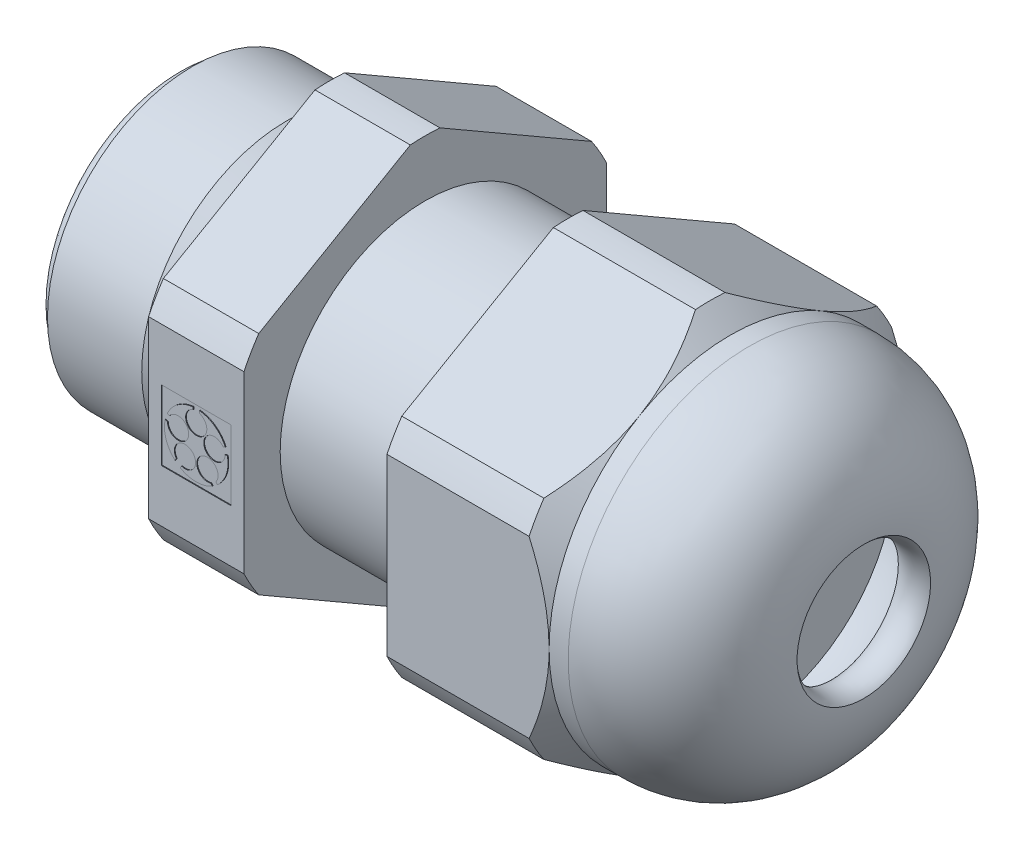
SolidWorks part; units mm, degrees
ref_plane "Face" through (0, 0, 0) normal (0, 0, 1) x (1, 0, 0)
ref_plane "Dessus" through (0, 0, 0) normal (0, 1, 0) x (1, 0, 0)
ref_plane "Droite" through (0, 0, 0) normal (1, 0, 0) x (0, 0, -1)
ref_plane "Plan1" through (0, 0, 0) normal (0, 0, 1) x (1, 0, 0)
sketch "Esquisse1" plane through (0, 0, 0) normal (0, 0, 1) x (1, 0, 0)
  line L0 (0.585, 1.75) -> (30, 1.75)
  line L1 (30, 1.75) -> (30, 7.6)
  line L2 (30, 9.5) -> (29, 9.5)
  line L3 (29, 9.5) -> (25.8333, 12.6667)
  line L4 (25.8333, 12.6667) -> (20.5, 12.6667)
  line L5 (20.5, 12.6667) -> (20.5, 7.6)
  line L6 (20.5, 7.6) -> (13, 7.6)
  line L7 (13, 7.6) -> (13, 12.6667)
  line L8 (13, 12.6667) -> (8, 12.6667)
  line L9 (8, 12.6667) -> (8, 7.22)
  line L10 (8, 7.22) -> (6.4, 7.22)
  line L11 (6.4, 7.22) -> (5.7418, 7.6)
  line L12 (5.7418, 7.6) -> (0.8, 7.6)
  line L13 (0.8, 7.6) -> (0.8, 7.22)
  line L14 (0.8, 7.22) -> (0.585, 7.22)
  line L15 (0, 6.635) -> (0, 2.335)
  line L16 (36, 0) -> (0, 0) construction
  arc A0 (0, 2.335) -> (0.585, 1.75) centre (0.585, 2.335) ccw
  arc A1 (30, 7.6) -> (33.968, 4.532) centre (30, 3.5) cw
  arc A2 (33.968, 4.532) -> (36, 3.5) centre (35.1543, 4.3514) ccw
  arc A3 (36, 3.5) -> (30, 9.5) centre (30, 3.5) ccw
  arc A4 (0.585, 7.22) -> (0, 6.635) centre (0.585, 6.635) ccw
revolve "Révolution1" add sketch "Esquisse1" angle 360 about L16
cosmetic thread "Représentation de filetage1" parameters "D1"=7.12, "D2"=14.44
cosmetic thread "Représentation de filetage2" parameters "D1"=5.6, "D2"=14.44
ref_plane "Plan2" through (8, 0, 0) normal (1, 0, 0) x (0, 0, -1)
sketch "Esquisse2" plane through (8, 0, 0) normal (1, 0, 0) x (0, 0, -1)
  line L0 (-19, -19) -> (19, -19)
  line L1 (19, -19) -> (19, 19)
  line L2 (19, 19) -> (-19, 19)
  line L3 (-19, 19) -> (-19, -19)
  line L4 (-9.5, 4.5883) -> (-9.5, -4.5883)
  line L5 (-8.7236, -5.9331) -> (-0.7764, -10.5214)
  line L6 (0.7764, -10.5214) -> (8.7236, -5.9331)
  line L7 (9.5, -4.5883) -> (9.5, 4.5883)
  line L8 (8.7236, 5.9331) -> (0.7764, 10.5214)
  line L9 (-0.7764, 10.5214) -> (-8.7236, 5.9331)
  arc A0 (-9.5, -4.5883) -> (-8.7236, -5.9331) centre (0, 0) ccw
  arc A1 (-0.7764, -10.5214) -> (0.7764, -10.5214) centre (0, 0) ccw
  arc A2 (8.7236, -5.9331) -> (9.5, -4.5883) centre (0, 0) ccw
  arc A3 (9.5, 4.5883) -> (8.7236, 5.9331) centre (0, 0) ccw
  arc A4 (0.7764, 10.5214) -> (-0.7764, 10.5214) centre (0, 0) ccw
  arc A5 (-8.7236, 5.9331) -> (-9.5, 4.5883) centre (0, 0) ccw
extrude "Enlèv. mat.-Extru.1" cut sketch "Esquisse2" along normal blind 36
ref_plane "Plan3" through (0, 0, 9.5) normal (0, 0, 1) x (1, 0, 0)
sketch "Esquisse3" plane through (0, 0, 9.5) normal (0, 0, 1) x (1, 0, 0)
  line L0 (8.6667, -1.8333) -> (12.3333, -1.8333)
  line L1 (12.3333, -1.8333) -> (12.3333, 1.8333)
  line L2 (12.3333, 1.8333) -> (8.6667, 1.8333)
  line L3 (8.6667, 1.8333) -> (8.6667, -1.8333)
  line L4 (9.3904, -1.2436) -> (9.4659, -1.1398)
  line L5 (9.7355, -1.3357) -> (9.6601, -1.4396)
  line L6 (11.3399, -1.4396) -> (11.2645, -1.3357)
  line L7 (11.5341, -1.1398) -> (11.6096, -1.2436)
  line L8 (12.1287, 0.3539) -> (12.0066, 0.3143)
  line L9 (11.9036, 0.6313) -> (12.0256, 0.671)
  line L10 (10.6667, 1.6583) -> (10.6667, 1.53)
  line L11 (10.3333, 1.53) -> (10.3333, 1.6583)
  line L12 (8.9744, 0.671) -> (9.0964, 0.6313)
  line L13 (8.9934, 0.3143) -> (8.8713, 0.3539)
  arc A0 (8.8713, 0.3539) -> (9.3904, -1.2436) centre (10.5, 0) ccw
  arc A1 (9.4659, -1.1398) -> (9.7355, -1.3357) centre (9.9122, -0.809) cw
  arc A2 (9.6601, -1.4396) -> (11.3399, -1.4396) centre (10.5, 0) ccw
  arc A3 (11.2645, -1.3357) -> (11.5341, -1.1398) centre (11.0878, -0.809) cw
  arc A4 (11.6096, -1.2436) -> (12.1287, 0.3539) centre (10.5, 0) ccw
  arc A5 (12.0066, 0.3143) -> (11.9036, 0.6313) centre (11.4511, 0.309) cw
  arc A6 (12.0256, 0.671) -> (10.6667, 1.6583) centre (10.5, 0) ccw
  arc A7 (10.6667, 1.53) -> (10.3333, 1.53) centre (10.5, 1) cw
  arc A8 (10.3333, 1.6583) -> (8.9744, 0.671) centre (10.5, 0) ccw
  arc A9 (9.0964, 0.6313) -> (8.9934, 0.3143) centre (9.5489, 0.309) cw
extrude "Enlèv. mat.-Extru.2" cut sketch "Esquisse3" against normal blind 0.038
